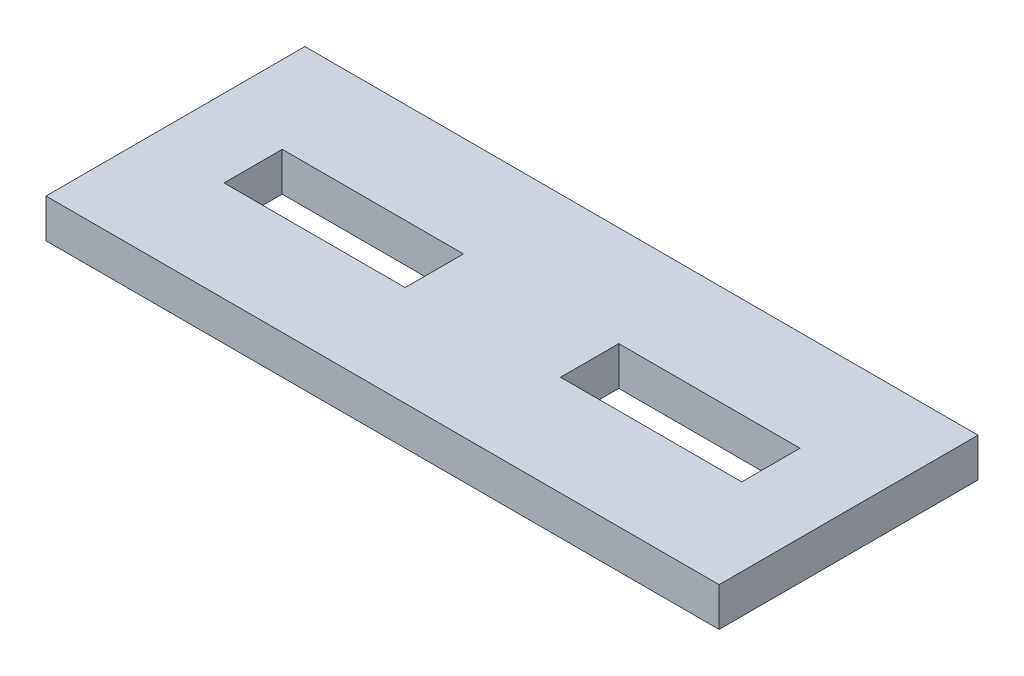
SolidWorks part; units mm, degrees
ref_plane "Front Plane" through (0, 0, 0) normal (0, 0, 1) x (1, 0, 0)
ref_plane "Top Plane" through (0, 0, 0) normal (0, 1, 0) x (1, 0, 0)
ref_plane "Right Plane" through (0, 0, 0) normal (1, 0, 0) x (0, 0, -1)
sketch "Sketch1" plane through (0, 0, 0) normal (0, 1, 0) x (1, 0, 0)
  line L1 (-26, -10) -> (26, -10)
  line L2 (-26, -10) -> (-26, 10)
  line L3 (-26, 10) -> (26, 10)
  line L4 (26, -10) -> (26, 10)
  line L5 (-20, -2.25) -> (-6, -2.25)
  line L6 (-20, -2.25) -> (-20, 2.25)
  line L7 (-20, 2.25) -> (-6, 2.25)
  line L8 (-6, -2.25) -> (-6, 2.25)
  line L9 (6, -2.25) -> (20, -2.25)
  line L10 (6, -2.25) -> (6, 2.25)
  line L11 (6, 2.25) -> (20, 2.25)
  line L12 (20, -2.25) -> (20, 2.25)
extrude "Slotted_Bracket_Extrude" add sketch "Sketch1" along normal blind 3
equation "\"ValveDiameter\" = 50mm"
equation "\"MotorGearTeeth\" = 40"
equation "\"OutputGearTeeth\" = 80"
equation "\"GearModule\" = 1.5mm"
equation "\"PressureAngle\" = 20deg"
equation "\"GearCenterDistance\" = 90mm"
equation "\"GearWidth\" = 18mm"
equation "\"OutputShaftDiameter\" = 20mm"
equation "\"BearingOD\" = 47mm"
equation "\"BearingWidth\" = 14mm"
equation "\"PlateThickness\" = 6mm"
equation "\"ValveRotation\" = 90deg"
